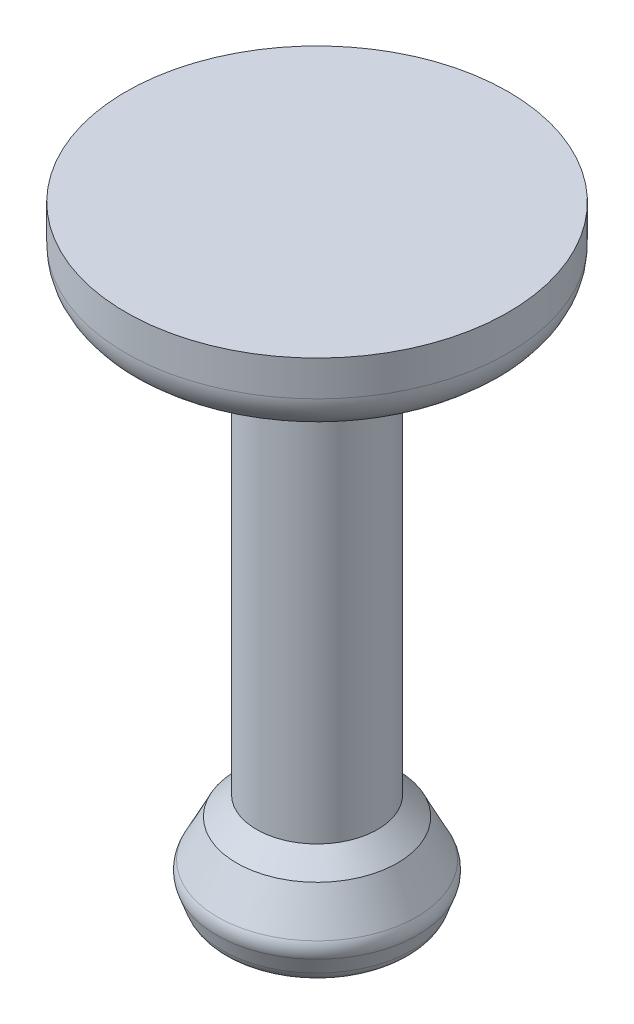
SolidWorks part; units mm, degrees
ref_plane "Front Plane" through (0, 0, 0) normal (0, 0, 1) x (1, 0, 0)
ref_plane "Top Plane" through (0, 0, 0) normal (0, 1, 0) x (1, 0, 0)
ref_plane "Right Plane" through (0, 0, 0) normal (1, 0, 0) x (0, 0, -1)
sketch "Sketch1" plane through (0, 0, 0) normal (0, 0, 1) x (1, 0, 0)
  line L0 (-20.4002, 14.4249) -> (-20.4002, -0.2614)
  line L1 (-16.3864, 33.7772) -> (-29.066, 33.7772)
  line L2 (-19.4537, -6.9245) -> (-21.4594, -6.9245)
  line L3 (-22.6533, -6.0875) -> (-23.0426, -5.0143)
  line L4 (-16.3864, -3.0528) -> (-16.3864, 109.7347) construction
  line L5 (-19.9852, -3.905) -> (-20.2433, -4.6457)
  line L6 (-20.1507, -5.6865) -> (-19.4537, -6.9245)
  line L7 (-18.7859, -3.0528) -> (-16.3864, -3.0528)
  line L8 (-16.3864, -3.0528) -> (-16.3864, 33.7772)
  line L9 (-16.3864, -3.0528) -> (-16.3864, -9.1664) construction
  line L11 (-22.9802, -4.0046) -> (-21.7192, -1.5305)
  line L12 (-29.066, 33.7772) -> (-29.066, 31.433)
  line L13 (-26.9136, 28.9228) -> (-22.5526, 28.2493)
  line L14 (-20.4002, 25.7391) -> (-20.4002, 14.4249)
  line L15 (-20.4002, -0.2614) -> (-21.7192, -1.5305)
  arc A0 (-26.9136, 28.9228) -> (-29.066, 31.433) centre (-26.526, 31.433) cw
  arc A1 (-20.1507, -5.6865) -> (-20.2433, -4.6457) centre (-19.044, -5.0635) cw
  arc A2 (-18.7859, -3.0528) -> (-19.9852, -3.905) centre (-18.7859, -4.3228) ccw
  arc A3 (-22.5526, 28.2493) -> (-20.4002, 25.7391) centre (-22.9402, 25.7391) cw
  arc A4 (-21.4594, -6.9245) -> (-22.6533, -6.0875) centre (-21.4594, -5.6545) cw
  arc A5 (-23.0426, -5.0143) -> (-22.9802, -4.0046) centre (-21.8486, -4.5813) cw
  point P10 (0, 0)
  dimension "D2" = 1.27
revolve "Revolve3" add sketch "Sketch1" angle 360 about L4
